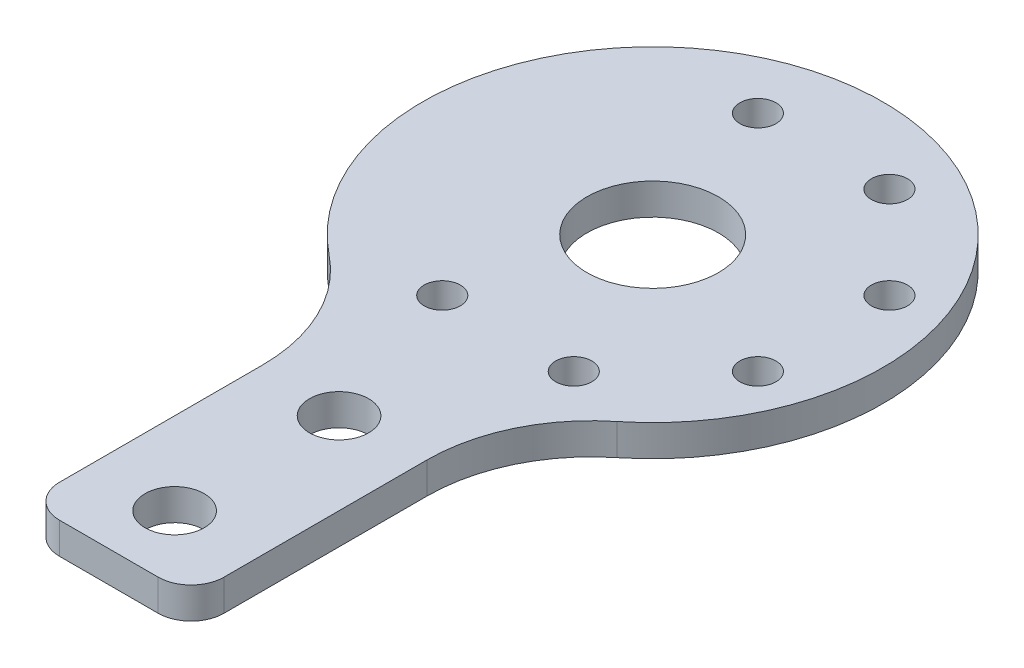
SolidWorks part; units mm, degrees
material "1060 Alloy"
ref_plane "Front Plane" through (0, 0, 0) normal (0, 0, 1) x (1, 0, 0)
ref_plane "Top Plane" through (0, 0, 0) normal (0, 1, 0) x (1, 0, 0)
ref_plane "Right Plane" through (0, 0, 0) normal (1, 0, 0) x (0, 0, -1)
sketch "Sketch1" plane through (0, 0, 0) normal (0, 1, 0) x (1, 0, 0)
  line L0 (-12.5, -82.6917) -> (12.5, -82.6917)
  line L1 (12.5, -82.6917) -> (12.5, -32.6917)
  line L2 (-12.5, -82.6917) -> (-12.5, -32.6917)
  arc A0 (12.5, -32.6917) -> (-12.5, -32.6917) centre (0, 0) ccw
  point P5 (0, -82.6917)
  dimension "D2" = 70
  dimension "D1" = 25
  dimension "D3" = 50
extrude "Boss-Extrude1" add sketch "Sketch1" along normal blind 4.7625 contours A0 L2 L0 L1
sketch "Sketch2" plane through (0, 0, 0) normal (0, -1, 0) x (1, 0, 0)
  line L0 (2.6194, 0) -> (-2.6194, 0) construction
  point P2 (0, 0)
  point P5 (-8, 24)
  point P13 (12, 24)
  point P14 (26, 10)
  point P16 (0, 0)
  point P22 (26, -10)
  point P23 (12, -24)
  point P24 (-8, -24)
  point P25 (0, 0)
  dimension "D2" = 26
  dimension "D1" = 8
  dimension "D3" = 20
  dimension "D4" = 10
  dimension "D5" = 24
sketch "Sketch5" plane through (0, 0, 0) normal (0, -1, 0) x (1, 0, 0)
  circle A0 centre (0, 0) radius 10
  dimension "D1" = 20
extrude "Cut-Extrude1" cut sketch "Sketch5" against normal through all
sketch "Sketch6" plane through (0, 0, 0) normal (0, -1, 0) x (1, 0, 0)
  line L0 (0, 82.6917) -> (0, 47.6917) construction
  line L1 (-12.5, 82.6917) -> (12.5, 82.6917) construction
  point P5 (0, 72.6917)
  dimension "D1" = 25
  dimension "D2" = 10
hole_wizard "M8 Clearance Hole1" positions "Sketch7" profile "Sketch8" hole size "M8" standard "ANSI Metric" end condition through all
sketch "Sketch7" plane through (0, 0, 0) normal (0, -1, 0) x (-1, 0, 0)
  point P0 (0, -47.6917)
  point P3 (0, -72.6917)
sketch "Sketch8" plane through (0, 0, 47.6917) normal (1, 0, 0) x (0, 0, -1)
  line L0 (0, 0) -> (0, 4.7625)
  line L1 (0, 4.7625) -> (4.5, 4.7625)
  line L2 (4.5, 4.7625) -> (4.5, 0)
  line L5 (4.5, 0) -> (0, 0)
  line L11 (0, -6.35) -> (0, 107.95) construction
  dimension "Thru Hole Dia." = 9
  dimension "Thru Hole Depth" = 4.7625
fillet "Fillet1" radius 25 2 edges at (-12.5, 2.3813, 32.6917) (12.5, 2.3813, 32.6917)
hole_wizard "M5 Clearance Hole1" positions "Sketch9" profile "Sketch10" hole size "M5" standard "ANSI Metric" end condition through all
sketch "Sketch9" plane through (0, 0, 0) normal (0, -1, 0) x (-1, 0, 0)
  point P18 (-12, 24)
  point P21 (8, 24)
  point P27 (-26, 10)
  point P30 (-26, -10)
  point P33 (-12, -24)
  point P36 (8, -24)
sketch "Sketch10" plane through (12, 0, -24) normal (1, 0, 0) x (0, 0, -1)
  line L0 (0, 0) -> (0, 4.7625)
  line L1 (0, 4.7625) -> (2.75, 4.7625)
  line L2 (2.75, 4.7625) -> (2.75, 0.025)
  line L3 (2.75, 0.025) -> (2.775, 0)
  line L5 (2.775, 0) -> (0, 0)
  line L6 (-2.75, 0.025) -> (-2.775, 0) construction
  line L11 (0, -6.35) -> (0, 107.95) construction
  dimension "Thru Hole Dia." = 5.5
  dimension "Thru Hole Depth" = 4.7625
  dimension "Near C'Sink Dia." = 5.55
  dimension "Near C'Sink Angle" = 90
fillet "Fillet2" radius 5 2 edges at (-12.5, 2.3813, 82.6917) (12.5, 2.3813, 82.6917)
